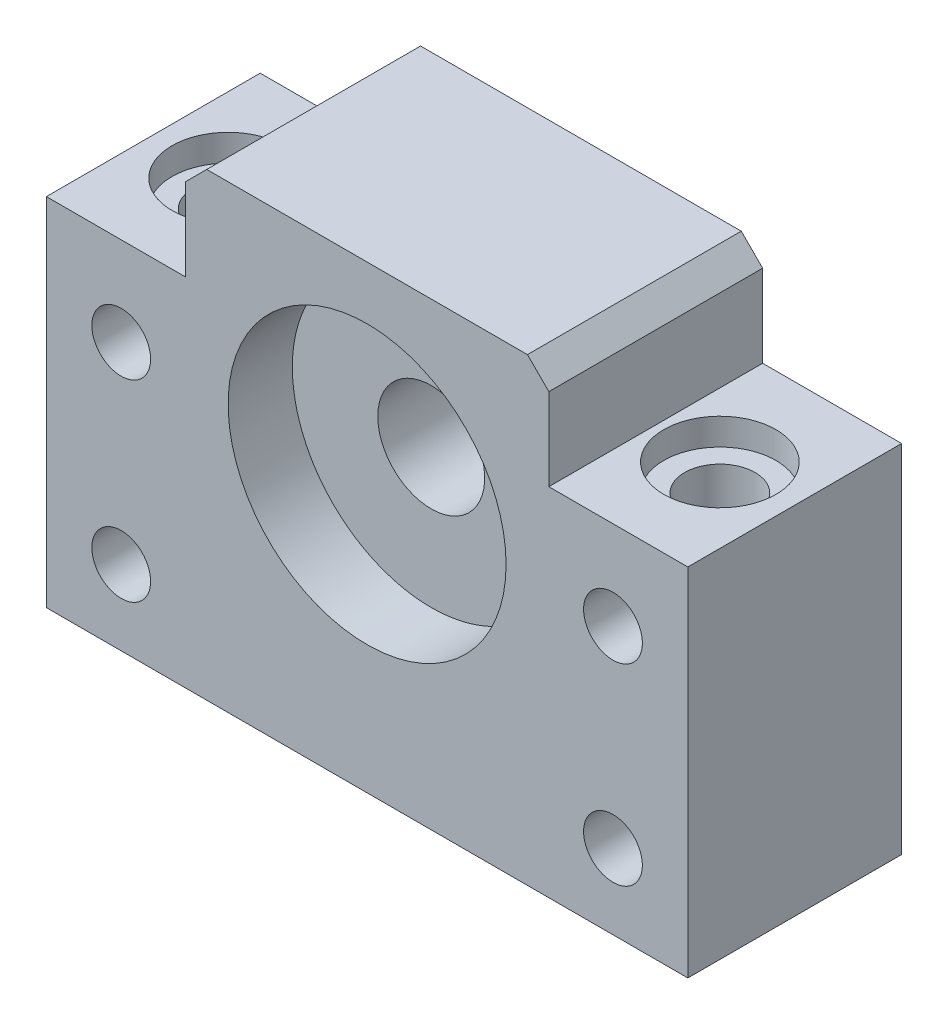
SolidWorks part; units mm, degrees
ref_plane "Ebene vorne" through (0, 0, 0) normal (0, 0, 1) x (1, 0, 0)
ref_plane "Ebene oben" through (0, 0, 0) normal (0, 1, 0) x (1, 0, 0)
ref_plane "Ebene rechts" through (0, 0, 0) normal (1, 0, 0) x (0, 0, -1)
sketch "Skizze1" plane through (0, 0, 0) normal (0, 0, 1) x (1, 0, 0)
  line L0 (0, 0) -> (0, 48.3079) construction
  line L1 (17, 41) -> (15, 43)
  line L2 (-30, 0) -> (30, 0)
  line L3 (30, 0) -> (30, 33.3)
  line L4 (30, 33.3) -> (17, 33.3)
  line L5 (17, 33.3) -> (17, 41)
  line L6 (15, 43) -> (-15, 43)
  line L7 (-17, 41) -> (-15, 43)
  line L8 (-17, 33.3) -> (-17, 41)
  line L9 (-30, 33.3) -> (-17, 33.3)
  line L10 (-30, 0) -> (-30, 33.3)
  line L11 (23, 25) -> (23, 7) construction
  circle A0 centre (0, 25) radius 13
  circle A1 centre (23, 25) radius 2.75
  circle A2 centre (23, 7) radius 2.75
  circle A3 centre (-23, 25) radius 2.75
  circle A4 centre (-23, 7) radius 2.75
  point P8 (17, 43)
  point P11 (0, 43)
  point P25 (0, 48.3079)
  dimension "D6" = 26
  dimension "D8" = 46
  dimension "D9" = 7
  dimension "D10" = 18
  dimension "D11" = 5.5
  dimension "D1" = 34
  dimension "D2" = 60
  dimension "D4" = 43
  dimension "D5" = 33.3
  dimension "D7" = 25
extrude "Aufsatz-Linear austragen1" add sketch "Skizze1" along normal mid plane 20
sketch "Skizze2" plane through (0, 0, -10) normal (0, 0, -1) x (-1, 0, 0)
  circle A0 centre (0, 25) radius 13 construction
  circle A1 centre (0, 25) radius 13
  circle A2 centre (0, 25) radius 5
  dimension "D1" = 10
extrude "Aufsatz-Linear austragen2" add sketch "Skizze2" against normal blind 8 from offset 6 separate body offset against normal yes
sketch "Skizze3" plane through (0, 33.3, 0) normal (0, 1, 0) x (1, 0, 0)
  line L0 (0, 0) -> (23, 0) construction
  line L1 (0, 0) -> (0, 14.3677) construction
  circle A0 centre (23, 0) radius 3.3
  circle A1 centre (-23, 0) radius 3.3
  dimension "D1" = 6.6
  dimension "D2" = 46
extrude "Schnitt-Linear austragen1" cut sketch "Skizze3" against normal blind 60
sketch "Skizze4" plane through (0, 33.3, 0) normal (0, 1, 0) x (1, 0, 0)
  line L0 (0, 0) -> (0, 15.392) construction
  circle A0 centre (23, 0) radius 5.25
  circle A1 centre (-23, 0) radius 5.25
  dimension "D1" = 10.5
extrude "Schnitt-Linear austragen2" cut sketch "Skizze4" against normal blind 2.5
